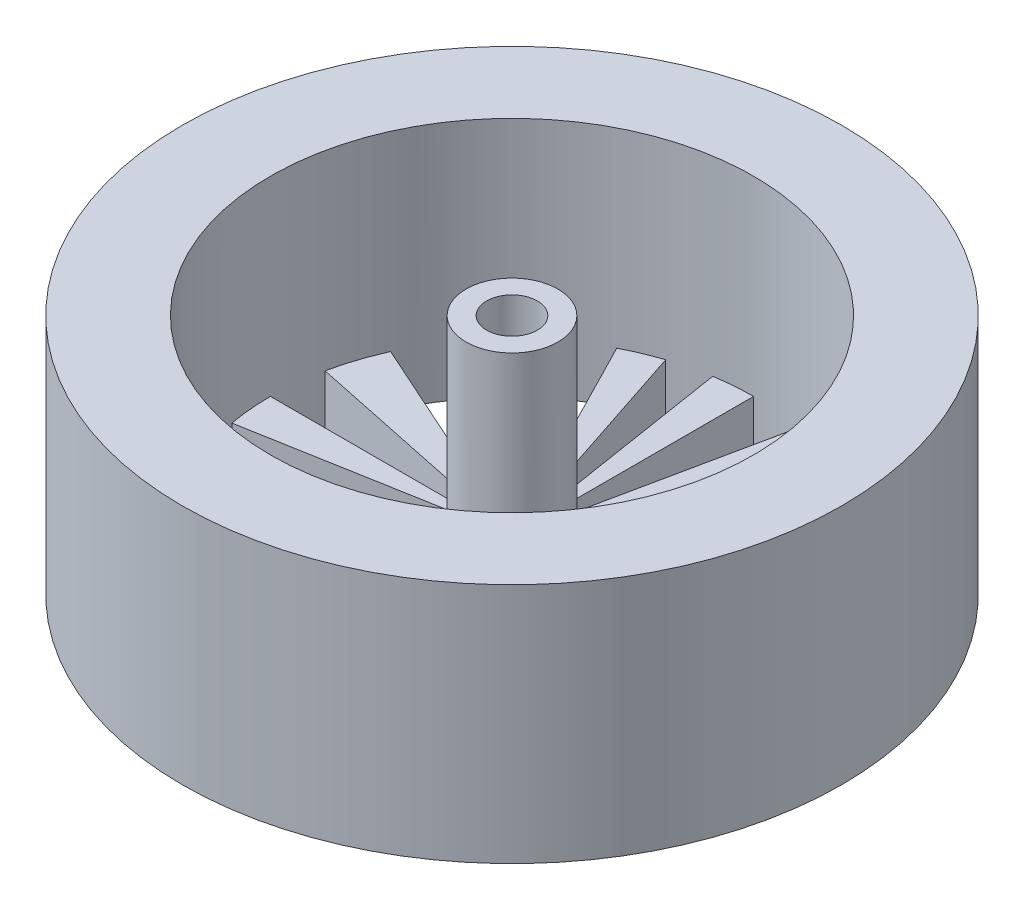
SolidWorks part; units mm, degrees
ref_plane "Front Plane" through (0, 0, 0) normal (0, 0, 1) x (1, 0, 0)
ref_plane "Top Plane" through (0, 0, 0) normal (0, 1, 0) x (1, 0, 0)
ref_plane "Right Plane" through (0, 0, 0) normal (1, 0, 0) x (0, 0, -1)
sketch "Sketch1" plane through (0, 0, 0) normal (0, 1, 0) x (1, 0, 0)
  circle A0 centre (0, 0) radius 34.671
  dimension "D1" = 69.342
extrude "Boss-Extrude1" add sketch "Sketch1" along normal blind 25.4
sketch "Sketch2" plane through (0, 25.4, 0) normal (0, 1, 0) x (1, 0, 0)
  circle A0 centre (0, 0) radius 25.4
  dimension "D1" = 50.8
extrude "Cut-Extrude1" cut sketch "Sketch2" against normal blind 20.066
sketch "Sketch4" plane through (0, 5.334, 0) normal (0, 1, 0) x (1, 0, 0)
  circle A0 centre (0, 0) radius 4.826
  dimension "D1" = 9.652
extrude "Boss-Extrude2" add sketch "Sketch4" along normal blind 20.066
sketch "Sketch5" plane through (0, 25.4, 0) normal (0, 1, 0) x (1, 0, 0)
  circle A0 centre (0, 0) radius 2.667
  dimension "D1" = 5.334
extrude "Cut-Extrude2" cut sketch "Sketch5" against normal blind 20.066
sketch "Sketch6" plane through (0, 5.334, 0) normal (0, 1, 0) x (1, 0, 0)
  line L0 (-25.4, 0) -> (0, 0)
  line L1 (0, 0) -> (25.4, 0)
  line L2 (0, 0) -> (0, 25.4)
  line L3 (0, 0) -> (0, -25.4)
  line L4 (0, 0) -> (-19.2407, -16.5818)
  line L5 (0, 0) -> (19.2407, 16.5818)
  line L6 (0, 0) -> (-15.914, 19.7966)
  line L7 (0, 0) -> (15.914, -19.7966)
  line L8 (0, 0) -> (-10.4052, -23.1709)
  line L9 (0, 0) -> (10.4052, 23.1709)
  line L10 (0, 0) -> (-23.1709, 10.4052)
  line L11 (0, 0) -> (23.1709, -10.4052)
  line L12 (0, 0) -> (-23.7867, -8.908)
  line L13 (0, 0) -> (23.7867, 8.908)
  line L14 (0, 0) -> (-7.957, 24.1215)
  line L15 (0, 0) -> (7.957, -24.1215)
  line L16 (0, 0) -> (-25.0064, -4.454)
  line L17 (0, 0) -> (-21.997, -12.7)
  line L18 (0, 0) -> (-15.914, -19.7966)
  line L19 (0, 0) -> (-5.2026, -24.8615)
  line L20 (0, 0) -> (2.5743, -25.2692)
  line L21 (0, 0) -> (11.5855, -22.6039)
  line L22 (0, 0) -> (19.7966, -15.914)
  line L23 (0, 0) -> (24.8615, -5.2026)
  line L24 (0, 0) -> (25.0064, 4.454)
  line L25 (0, 0) -> (21.997, 12.7)
  line L26 (0, 0) -> (14.7588, 20.6721)
  line L27 (0, 0) -> (5.2026, 24.8615)
  line L28 (0, 0) -> (-3.9785, 25.0865)
  line L29 (0, 0) -> (-11.5855, 22.6039)
  line L30 (0, 0) -> (-20.6721, 14.7588)
  line L31 (0, 0) -> (-24.8615, 5.2026)
  circle A0 centre (0, 0) radius 25.4 construction
  circle A1 centre (0, 0) radius 25.4 construction
  circle M1 centre (0, 0) radius 4.826
  circle M2 centre (0, 0) radius 25.4
extrude "Cut-Extrude3" cut sketch "Sketch6" against normal through all contours L30 L10 M1 M2 | L29 L6 M1 M2 | L28 L14 M1 M2 | L27 L2 M1 M2 | L26 L9 M1 M2 | L25 L5 M1 M2 | L24 L13 M1 M2 | L23 L1 M1 M2 | L22 L11 M1 M2 | L21 L7 M1 M2 | L20 L15 M1 M2 | L19 L3 M1 M2 | L18 L8 M1 M2 | L17 L4 M1 M2 | L16 L12 M1 M2 | L31 L0 M1 M2
